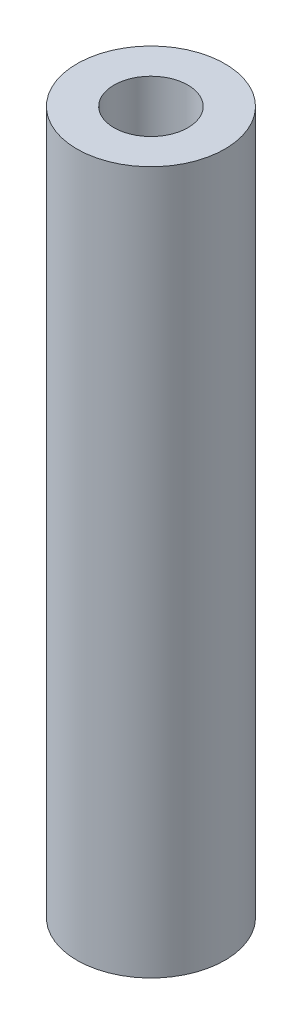
SolidWorks part; units mm, degrees
ref_plane "Front Plane" through (0, 0, 0) normal (0, 0, 1) x (1, 0, 0)
ref_plane "Top Plane" through (0, 0, 0) normal (0, 1, 0) x (1, 0, 0)
ref_plane "Right Plane" through (0, 0, 0) normal (1, 0, 0) x (0, 0, -1)
sketch "Sketch1" plane through (0, 0, 0) normal (0, 1, 0) x (1, 0, 0)
  circle A0 centre (0, 0) radius 1
  circle A1 centre (0, 0) radius 2
  dimension "D1" = 2
  dimension "D2" = 4
extrude "Boss-Extrude1" add sketch "Sketch1" along normal blind 19
chamfer "Chamfer1" distance 2 angle 20 1 edges at (0, 0, 1)
